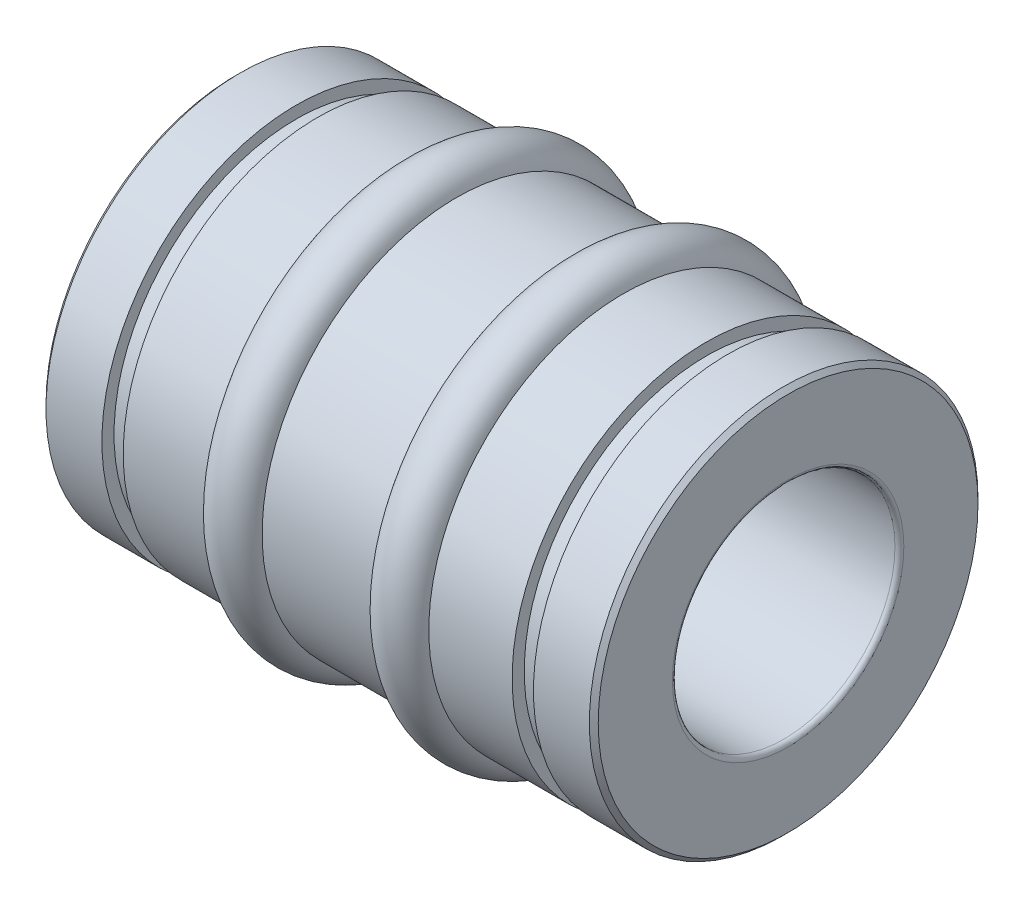
SolidWorks part; units mm, degrees
material "6063-T6"
ref_plane "Front Plane" through (0, 0, 0) normal (0, 0, 1) x (1, 0, 0)
ref_plane "Top Plane" through (0, 0, 0) normal (0, 1, 0) x (1, 0, 0)
ref_plane "Right Plane" through (0, 0, 0) normal (1, 0, 0) x (0, 0, -1)
ref_plane "Plane1" through (0, 0, 0) normal (0, 0, 1) x (1, 0, 0)
sketch "Sketch1" plane through (0, 0, 0) normal (0, 0, 1) x (1, 0, 0)
  line L0 (-15.7797, 10.8521) -> (-15.7797, 6.6142)
  line L1 (-15.5258, 6.3602) -> (15.5258, 6.3602)
  line L2 (15.7797, 6.6142) -> (15.7797, 10.8521)
  line L3 (15.7797, 10.8521) -> (15.5258, 11.1061)
  line L4 (15.5258, 11.1061) -> (12.3317, 11.1061)
  line L5 (12.3317, 11.1061) -> (12.3317, 10.414)
  line L6 (12.3317, 10.414) -> (11.1125, 10.414)
  line L7 (11.1125, 10.414) -> (11.1125, 11.1061)
  line L8 (11.1125, 11.1061) -> (6.35, 11.1061)
  line L9 (6.35, 11.1061) -> (6.35, 9.0424)
  line L10 (6.35, 9.0424) -> (3.175, 9.0424)
  line L11 (3.175, 9.0424) -> (3.175, 11.1061)
  line L12 (3.175, 11.1061) -> (-3.175, 11.1061)
  line L13 (-3.175, 11.1061) -> (-3.175, 9.0424)
  line L14 (-3.175, 9.0424) -> (-6.35, 9.0424)
  line L15 (-6.35, 9.0424) -> (-6.35, 11.1061)
  line L16 (-6.35, 11.1061) -> (-11.1125, 11.1061)
  line L17 (-11.1125, 11.1061) -> (-11.1125, 10.414)
  line L18 (-11.1125, 10.414) -> (-12.3317, 10.414)
  line L19 (-12.3317, 10.414) -> (-12.3317, 11.1061)
  line L20 (-12.3317, 11.1061) -> (-15.5258, 11.1061)
  line L21 (-15.5258, 11.1061) -> (-15.7797, 10.8521)
  line L22 (15.7797, 0) -> (-15.7797, 0) construction
  arc A0 (-15.7797, 6.6142) -> (-15.5258, 6.3602) centre (-15.5257, 6.6142) ccw
  arc A1 (15.5258, 6.3602) -> (15.7797, 6.6142) centre (15.5257, 6.6142) ccw
revolve "Revolve1" add sketch "Sketch1" angle 360 about L22
sketch "Sketch2" plane through (0, 0, 0) normal (0, 1, 0) x (1, 0, 0)
  line L0 (-3.175, 9.0424) -> (-6.35, 9.0424) construction
  circle A0 centre (-4.7625, 10.6299) radius 1.5875
  circle A1 centre (4.7625, 10.6299) radius 1.5875
  point P2 (-4.7625, 9.0424)
ref_axis "Axis1" through (-15.5258, 0, 0) along (1, 0, 0)
revolve "Revolve2" add sketch "Sketch2" angle 360 about axis through (-15.5258, 0, 0) along (1, 0, 0)
